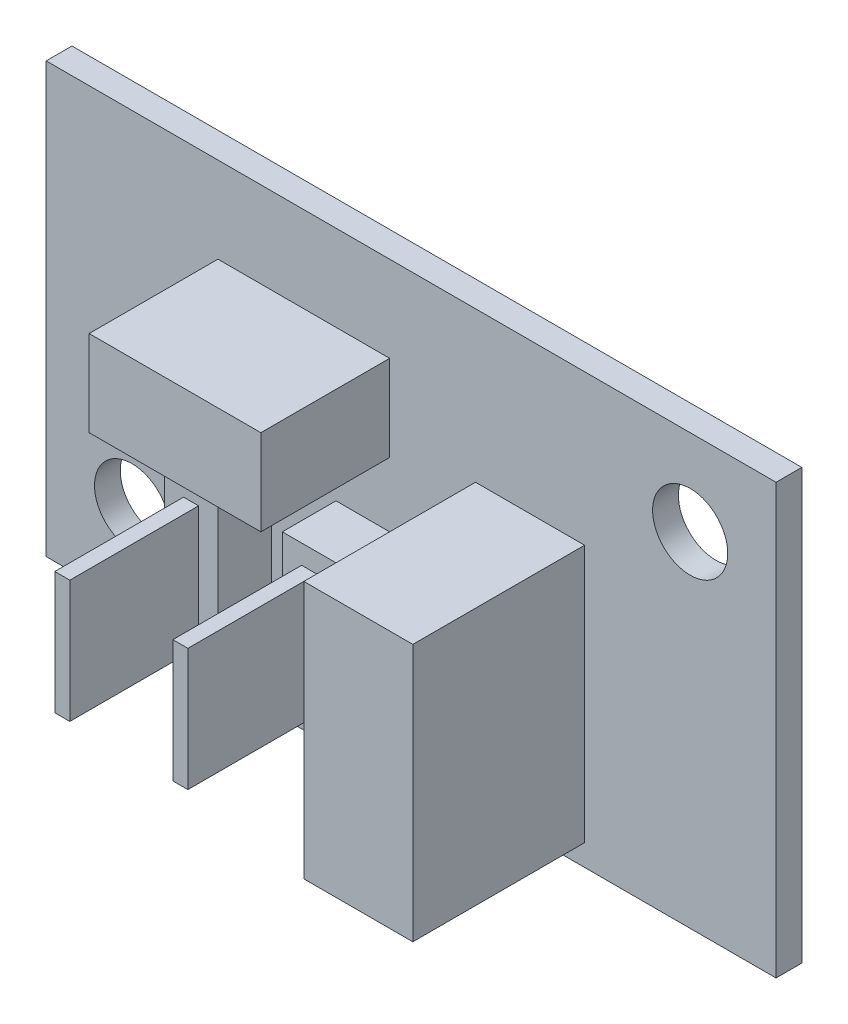
SolidWorks part; units mm, degrees
ref_plane "Top Plane" through (0, 0, 0) normal (0, 0, 1) x (1, 0, 0)
ref_plane "Right Plane" through (0, 0, 0) normal (0, 1, 0) x (1, 0, 0)
ref_plane "Front Plane" through (0, 0, 0) normal (1, 0, 0) x (0, 0, -1)
sketch "Sketch1" plane through (0, 0, 0) normal (0, 0, 1) x (1, 0, 0)
  line L0 (-17, 10) -> (17, -10) construction
  line L1 (-17, 10) -> (17, 10)
  line L2 (-17, 10) -> (-17, -10)
  line L3 (-17, -10) -> (17, -10)
  line L4 (17, 10) -> (17, -10)
  dimension "D1" = 34
  dimension "D2" = 20
extrude "Boss-Extrude1" add sketch "Sketch1" along normal mid plane 1.2
sketch "Sketch2" plane through (0, 0, 0.6) normal (0, 0, 1) x (1, 0, 0)
  line L0 (-5, -10) -> (-5, 10) construction
  line L1 (-9, -8.5) -> (-6.5, -8.5)
  line L2 (-9, -8.5) -> (-9, -1)
  line L3 (-9, -1) -> (-6.5, -1)
  line L4 (-6.5, -8.5) -> (-6.5, -1)
  line L5 (-17, -10) -> (17, -10) construction
  line L12 (-9, -4.75) -> (-8.67, -4.75) construction
  line L13 (-3.5, -8.5) -> (-3.5, -1)
  line L14 (-1, -1) -> (-3.5, -1)
  line L15 (-1, -8.5) -> (-1, -1)
  line L16 (-1, -8.5) -> (-3.5, -8.5)
  line L17 (-17, 10) -> (-17, -10) construction
  dimension "D1" = 2.5
  dimension "D2" = 7.5
  dimension "D3" = 1.5
  dimension "D4" = 3
  dimension "D5" = 12
extrude "Boss-Extrude2" add sketch "Sketch2" along normal blind 2.5
sketch "Sketch3" plane through (0, 0, 3.1) normal (0, 0, 1) x (1, 0, 0)
  line L8 (-8.1, -1.9) -> (-8.1, -7.6)
  line L9 (-8.1, -7.6) -> (-7.4, -7.6)
  line L10 (-7.4, -7.6) -> (-7.4, -1.9)
  line L11 (-7.4, -1.9) -> (-8.1, -1.9)
  line L12 (-8.1, -1.9) -> (-8.1, -7.6)
  line L13 (-8.1, -7.6) -> (-7.4, -7.6)
  line L14 (-7.4, -7.6) -> (-7.4, -1.9)
  line L15 (-7.4, -1.9) -> (-8.1, -1.9)
  line L32 (-2.6, -7.6) -> (-1.9, -7.6)
  line L33 (-1.9, -7.6) -> (-1.9, -1.9)
  line L34 (-1.9, -1.9) -> (-2.6, -1.9)
  line L35 (-2.6, -1.9) -> (-2.6, -7.6)
  line L36 (-2.6, -7.6) -> (-1.9, -7.6)
  line L37 (-1.9, -7.6) -> (-1.9, -1.9)
  line L38 (-1.9, -1.9) -> (-2.6, -1.9)
  line L39 (-2.6, -1.9) -> (-2.6, -7.6)
  dimension "D1" = 0.9
  dimension "D3" = 0.9
extrude "Boss-Extrude3" add sketch "Sketch3" along normal blind 6
sketch "Sketch4" plane through (0, 0, -0.6) normal (0, 0, -1) x (-1, 0, 0)
  line L0 (7.4, -1.9) -> (8.1, -1.9) construction
  line L1 (7.4, -7.6) -> (7.4, -1.9) construction
  line L2 (8.1, -7.6) -> (7.4, -7.6) construction
  line L3 (8.1, -1.9) -> (8.1, -7.6) construction
  line L8 (1.9, -7.6) -> (1.9, -1.9) construction
  line L9 (2.6, -7.6) -> (1.9, -7.6) construction
  line L10 (2.6, -1.9) -> (2.6, -7.6) construction
  line L11 (1.9, -1.9) -> (2.6, -1.9) construction
  line L12 (7.4, -1.9) -> (8.1, -1.9)
  line L13 (7.4, -7.6) -> (7.4, -1.9)
  line L14 (8.1, -7.6) -> (7.4, -7.6)
  line L15 (8.1, -1.9) -> (8.1, -7.6)
  line L20 (1.9, -7.6) -> (1.9, -1.9)
  line L21 (2.6, -7.6) -> (1.9, -7.6)
  line L22 (2.6, -1.9) -> (2.6, -7.6)
  line L23 (1.9, -1.9) -> (2.6, -1.9)
extrude "Boss-Extrude4" add sketch "Sketch4" along normal blind 1
sketch "Sketch6" plane through (0, 0, 0.6) normal (0, 0, 1) x (1, 0, 0)
  line L1 (3, -9) -> (8.08, -9)
  line L2 (3, -9) -> (3, 3)
  line L3 (3, 3) -> (8.08, 3)
  line L4 (8.08, -9) -> (8.08, 3)
  line L5 (-5, -10) -> (-5, 10) construction
  line L6 (-17, -10) -> (17, -10) construction
  dimension "D1" = 5.08
  dimension "D2" = 12
  dimension "D3" = 8
  dimension "D4" = 1
extrude "Boss-Extrude5" add sketch "Sketch6" along normal blind 8
sketch "Sketch7" plane through (0, 0, 0.6) normal (0, 0, 1) x (1, 0, 0)
  line L0 (-9, 6) -> (-1, 2) construction
  line L1 (-9, 6) -> (-1, 6)
  line L2 (-9, 6) -> (-9, 2)
  line L3 (-9, 2) -> (-1, 2)
  line L4 (-1, 6) -> (-1, 2)
  line L5 (-5, -10) -> (-5, 10) construction
  line L7 (-9, -1) -> (-6.5, -1) construction
  point P4 (-5, 4)
  dimension "D1" = 8
  dimension "D2" = 4
  dimension "D3" = 3
extrude "Boss-Extrude6" add sketch "Sketch7" along normal blind 6
sketch "Sketch8" plane through (0, 0, 0.6) normal (0, 0, 1) x (1, 0, 0)
  line L0 (-17, 0) -> (17, 0) construction
  line L1 (-17, 10) -> (-17, -10) construction
  line L2 (17, -10) -> (17, 10) construction
  line L3 (0, -10) -> (0, 10) construction
  line L4 (-17, -10) -> (17, -10) construction
  line L5 (17, 10) -> (-17, 10) construction
  circle A0 centre (-13, -6) radius 1.75
  circle A1 centre (13, -6) radius 1.75 construction
  circle A2 centre (13, 6) radius 1.75
  dimension "D1" = 3.5
  dimension "D2" = 4
  dimension "D3" = 4
extrude "Cut-Extrude1" cut sketch "Sketch8" against normal through all
